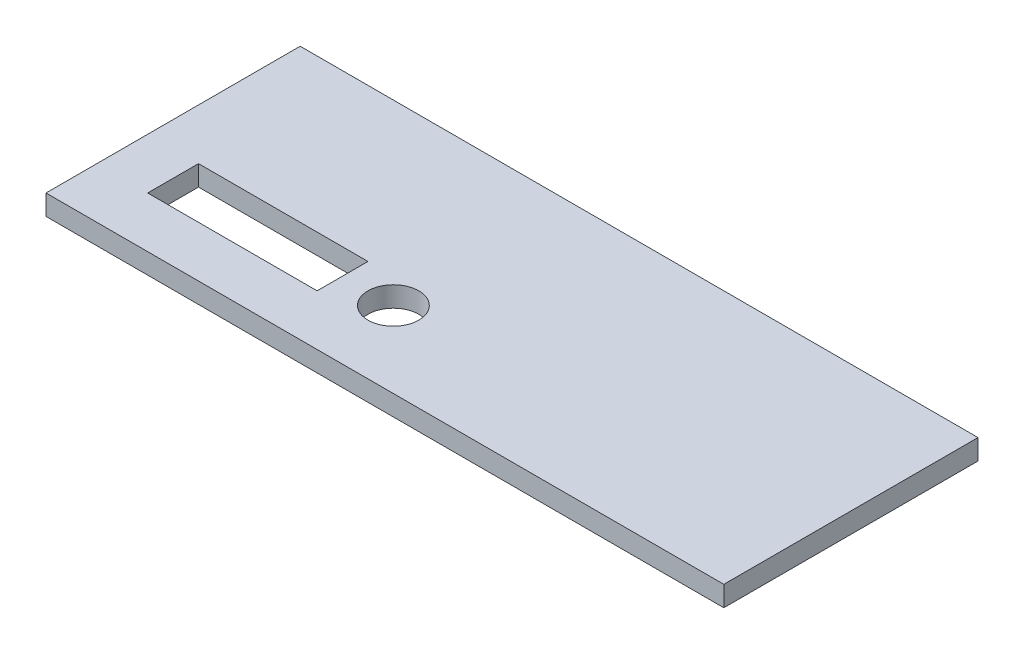
SolidWorks part; units mm, degrees
material "Pine"
ref_plane "Front Plane" through (0, 0, 0) normal (0, 0, 1) x (1, 0, 0)
ref_plane "Top Plane" through (0, 0, 0) normal (0, 1, 0) x (1, 0, 0)
ref_plane "Right Plane" through (0, 0, 0) normal (1, 0, 0) x (0, 0, -1)
sketch "Sketch1" plane through (0, 0, 0) normal (0, 1, 0) x (1, 0, 0)
  line L1 (0, 0) -> (200, 0)
  line L2 (0, 0) -> (0, 75)
  line L3 (0, 75) -> (200, 75)
  line L4 (200, 0) -> (200, 75)
  dimension "D1" = 75
  dimension "D2" = 200
extrude "Boss-Extrude1" add sketch "Sketch1" along normal blind 6
sketch "Sketch2" plane through (0, 6, 0) normal (0, 1, 0) x (1, 0, 0)
  line L0 (0, 0) -> (200, 0) construction
  line L1 (15, 15) -> (65, 15)
  line L2 (15, 15) -> (15, 30)
  line L3 (15, 30) -> (65, 30)
  line L4 (65, 15) -> (65, 30)
  line L5 (0, 75) -> (0, 0) construction
  circle A0 centre (80, 22.5) radius 7.5
  dimension "D5" = 15
  dimension "D1" = 15
  dimension "D2" = 15
  dimension "D3" = 50
  dimension "D4" = 15
  dimension "D6" = 22.5
  dimension "D7" = 15
extrude "Cut-Extrude1" cut sketch "Sketch2" against normal through all
equation "\"BoardThickness\"= 6"
equation "\"D1@Boss-Extrude1\"=\"BoardThickness\""
